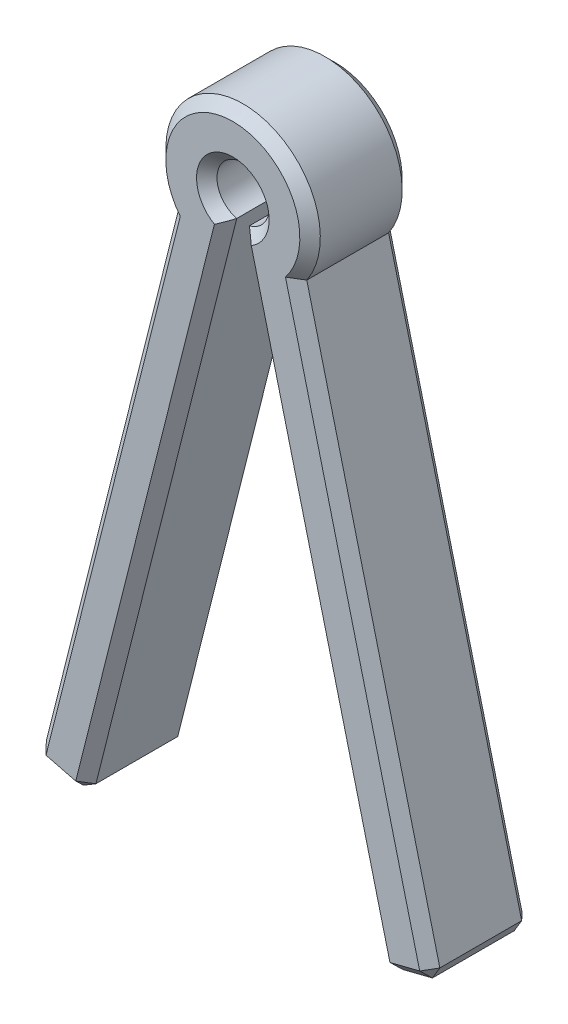
SolidWorks part; units mm, degrees
ref_plane "前视基准面" through (0, 0, 0) normal (0, 0, 1) x (1, 0, 0)
ref_plane "上视基准面" through (0, 0, 0) normal (0, 1, 0) x (1, 0, 0)
ref_plane "右视基准面" through (0, 0, 0) normal (1, 0, 0) x (0, 0, -1)
other "Configuration Table"
sketch "草图1" plane through (0, 0, 0) normal (0, 0, 1) x (1, 0, 0)
  line L0 (0, 0) -> (0, -17.8693) construction
  line L1 (-0.6218, -2.473) -> (-14.6311, -58.1887)
  line L2 (0.6218, -2.473) -> (14.6311, -58.1887)
  arc A0 (0.6218, -2.473) -> (-0.6218, -2.473) centre (0, 0) ccw
  dimension "D1" = 5.1
  dimension "D2" = 60
extrude "拉伸-薄壁1" add sketch "草图1" along normal blind 10 thin
chamfer "倒角1" distance 1 angle 45 20 edges at (-17.0557, -57.5791, 0) (-7.6265, -30.3309, 0) (0, 2.55, 0) (7.6265, -30.3309, 0) (17.0557, -57.5791, 0) (12.8544, -30.6183, 0) (0, 7.55, 0) (-12.8544, -30.6183, 0) (0, 7.55, 10) (12.8544, -30.6183, 10) (17.0557, -57.5791, 10) (7.6265, -30.3309, 10) (0, 2.55, 10) (-7.6265, -30.3309, 10) (-17.0557, -57.5791, 10) (-12.8544, -30.6183, 10) (19.4802, -56.9695, 5) (14.6311, -58.1887, 5) (-14.6311, -58.1887, 5) (-19.4802, -56.9695, 5)
